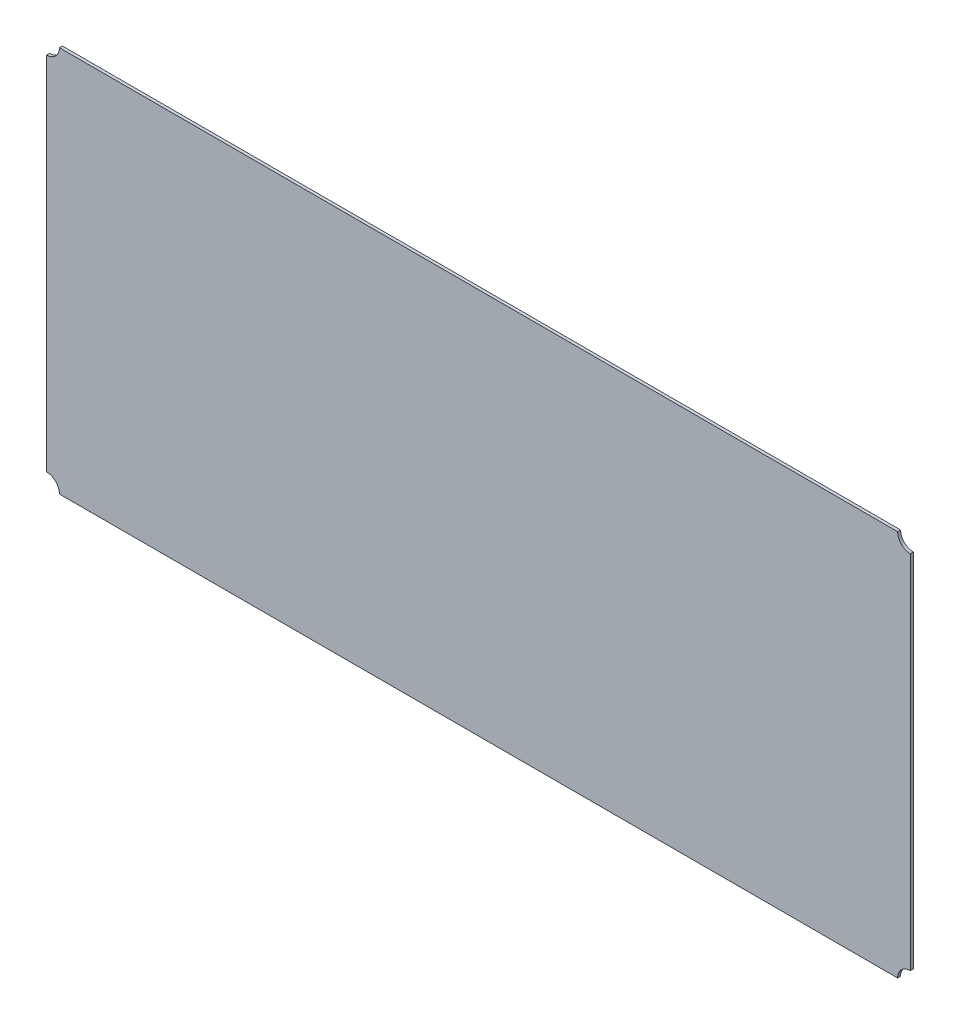
SolidWorks part; units mm, degrees
ref_plane "Front Plane" through (0, 0, 0) normal (0, 0, 1) x (1, 0, 0)
ref_plane "Top Plane" through (0, 0, 0) normal (0, 1, 0) x (1, 0, 0)
ref_plane "Right Plane" through (0, 0, 0) normal (1, 0, 0) x (0, 0, -1)
sketch "Sketch1" plane through (0, 0, 0) normal (0, 0, 1) x (1, 0, 0)
  line L1 (441.25, -197.5) -> (-441.25, -197.5)
  line L2 (441.25, -197.5) -> (441.25, 197.5)
  line L3 (441.25, 197.5) -> (-441.25, 197.5)
  line L4 (-441.25, -197.5) -> (-441.25, 197.5)
  line L5 (441.25, -197.5) -> (-441.25, 197.5) construction
  line L6 (441.25, 197.5) -> (-441.25, -197.5) construction
  point P0 (0, 0)
extrude "Boss-Extrude1" add sketch "Sketch1" against normal blind 3
sketch "Sketch3" plane through (0, 0, 0) normal (0, 0, 1) x (1, 0, 0)
  circle A0 centre (441.25, -197.5) radius 13
  circle A1 centre (441.25, 197.5) radius 13
  circle A2 centre (-441.25, 197.5) radius 13
  circle A3 centre (-441.25, -197.5) radius 13
  dimension "D1" = 26
extrude "Cut-Extrude1" cut sketch "Sketch3" against normal through all both and the other way through all
